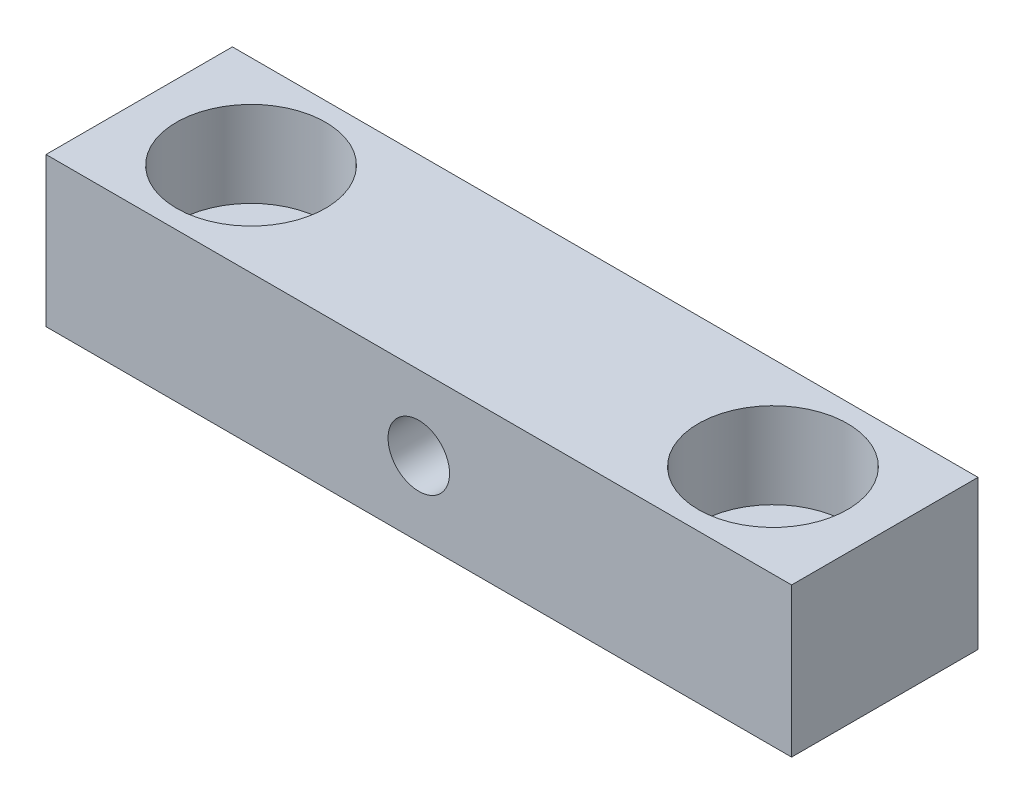
SolidWorks part; units mm, degrees
ref_plane "前视基准面" through (0, 0, 0) normal (0, 0, 1) x (1, 0, 0)
ref_plane "上视基准面" through (0, 0, 0) normal (0, 1, 0) x (1, 0, 0)
ref_plane "右视基准面" through (0, 0, 0) normal (1, 0, 0) x (0, 0, -1)
sketch "草图1" plane through (0, 0, 0) normal (0, 1, 0) x (1, 0, 0)
  line L1 (-20, -5) -> (20, -5)
  line L2 (-20, -5) -> (-20, 5)
  line L3 (-20, 5) -> (20, 5)
  line L4 (20, -5) -> (20, 5)
  line L5 (-20, -5) -> (20, 5) construction
  line L6 (-20, 5) -> (20, -5) construction
  point P0 (0, 0)
  dimension "D1" = 40
  dimension "D2" = 10
extrude "凸台-拉伸1" add sketch "草图1" along normal blind 8
hole_wizard "打孔尺寸(%根据)内六角圆柱头螺钉的类型1" positions "草图5" profile "草图4" counterbore size "M4" standard "GB" end condition up to next
sketch "草图5" plane through (0, 8, 0) normal (0, 1, 0) x (1, 0, 0)
  line L0 (0, 0) -> (0, 13.6167) construction
  line L2 (20, -5) -> (20, 5) construction
  point P0 (14, 0)
  point P9 (-14, 0)
  dimension "D1" = 6
sketch "草图4" plane through (14, 8, 0) normal (1, 0, 0) x (0, 0, 1)
  line L0 (0, 0) -> (0, 8)
  line L1 (0, 8) -> (2.25, 8)
  line L3 (2.25, 8) -> (2.25, 4.6)
  line L4 (2.25, 4.6) -> (4, 4.6)
  line L5 (4, 4.6) -> (4, 0)
  line L7 (4, 0) -> (0, 0)
  line L11 (0, -6.35) -> (0, 107.95) construction
  dimension "通孔孔直径" = 4.5
  dimension "通孔孔深度" = 8
  dimension "柱形沉头孔直径" = 8
  dimension "柱形沉头孔深度" = 4.6
hole_wizard "M4 螺纹孔1" positions "草图7" profile "草图6" tap size "M4" standard "GB" end condition up to next
sketch "草图7" plane through (0, 0, 5) normal (0, 0, 1) x (1, 0, 0)
  line L0 (20, 4) -> (-20, 4) construction
  line L1 (20, 8) -> (20, 0) construction
  line L2 (-20, 8) -> (-20, 0) construction
  point P0 (0, 4)
sketch "草图6" plane through (0, 4, 5) normal (1, 0, 0) x (0, -1, 0)
  line L0 (0, 0) -> (0, 10)
  line L1 (0, 10) -> (1.65, 10)
  line L2 (1.65, 10) -> (1.65, 0)
  line L5 (1.65, 0) -> (0, 0)
  line L11 (0, -6.35) -> (0, 107.95) construction
  dimension "通孔螺纹孔钻头直径" = 3.3
  dimension "通孔螺纹孔钻头深度" = 10
cosmetic thread "孔螺蚊线1" parameters "D2"=4
